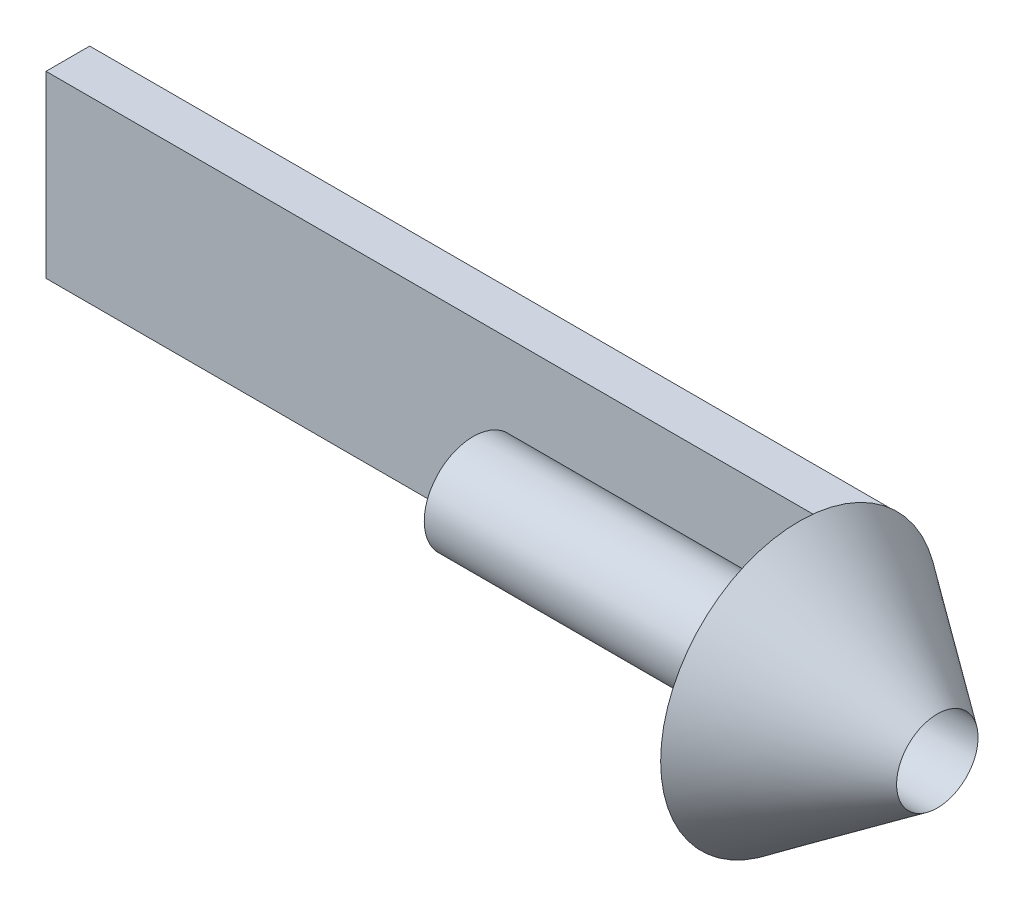
SolidWorks part; units mm, degrees
ref_plane "前基準面" through (0, 0, 0) normal (0, 0, 1) x (1, 0, 0)
ref_plane "上基準面" through (0, 0, 0) normal (0, 1, 0) x (1, 0, 0)
ref_plane "右基準面" through (0, 0, 0) normal (1, 0, 0) x (0, 0, -1)
sketch "草圖1" plane through (0, 0, 0) normal (0, 0, 1) x (1, 0, 0)
  line L1 (0, 8.5) -> (0, 0)
  line L3 (0, 0) -> (12, 0)
  line L4 (12, 0) -> (0, 8.5)
  dimension "D1" = 8.5
  dimension "D2" = 12
revolve "旋轉2" add sketch "草圖1" angle 360 about L3
sketch "草圖2" plane through (0, 0, 0) normal (-1, 0, 0) x (0, 0, 1)
  circle A0 centre (0, 0) radius 3.5
  circle A1 centre (0, 0) radius 2.5
  dimension "D1" = 5
  dimension "D2" = 7
extrude "除料-伸長3" cut sketch "草圖2" against normal blind 20 contours A1
sketch "草圖4" plane through (0, 0, 0) normal (-1, 0, 0) x (0, 0, 1)
  circle A0 centre (0, 0) radius 2.5
  circle A1 centre (0, 0) radius 3
  dimension "D1" = 5
extrude "填料-伸長1" add sketch "草圖4" along normal blind 20
sketch "草圖5" plane through (0, 0, 0) normal (-1, 0, 0) x (0, 0, 1)
  line L0 (-6.4807, 5.5) -> (-6.4807, -5.5)
  line L1 (-6.4807, 5.5) -> (-3.8, 5.5)
  line L2 (-6.4807, -5.5) -> (-3.8, -5.5)
  line L3 (-3.8, 5.5) -> (-3.8, -5.5)
  circle A0 centre (0, 0) radius 8.5 construction
  dimension "D2" = 3.8
  dimension "D1" = 11
extrude "填料-伸長2" add sketch "草圖5" along normal blind 50
